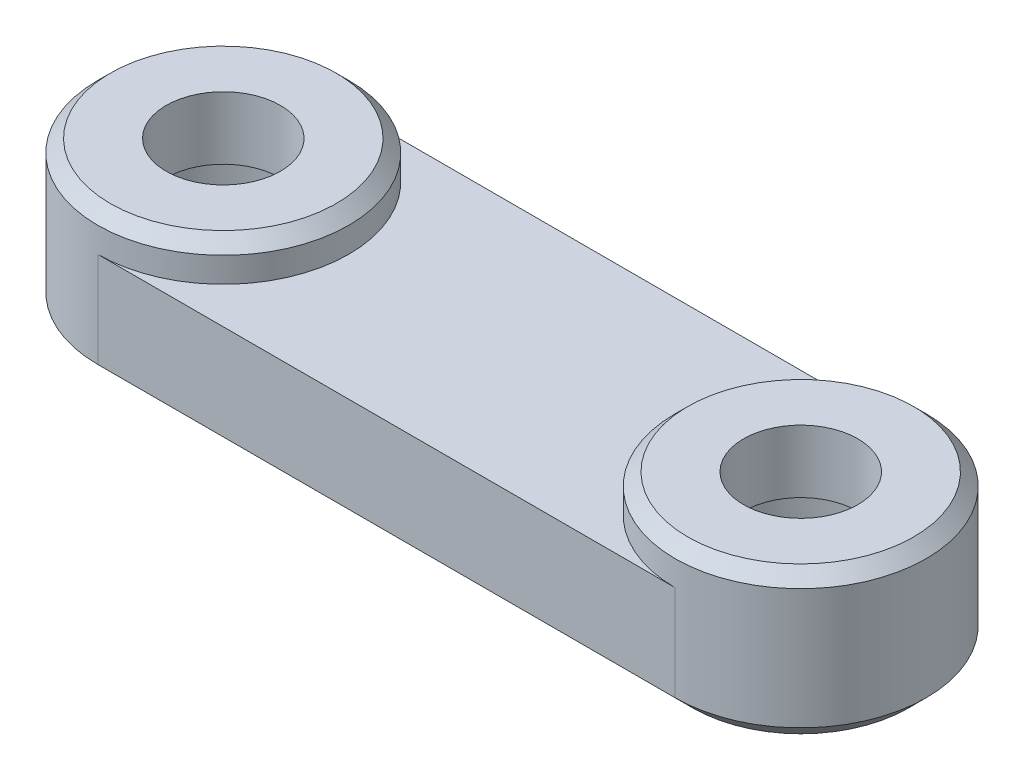
SolidWorks part; units mm, degrees
ref_plane "前视基准面" through (0, 0, 0) normal (0, 0, 1) x (1, 0, 0)
ref_plane "上视基准面" through (0, 0, 0) normal (0, 1, 0) x (1, 0, 0)
ref_plane "右视基准面" through (0, 0, 0) normal (1, 0, 0) x (0, 0, -1)
sketch "草图1" plane through (0, 0, 0) normal (0, 1, 0) x (1, 0, 0)
  line L0 (0, 0) -> (23, 0) construction
  line L1 (0, 5) -> (23, 5)
  line L2 (0, -5) -> (23, -5)
  arc A0 (0, 5) -> (0, -5) centre (0, 0) ccw
  arc A1 (23, -5) -> (23, 5) centre (23, 0) ccw
  point P3 (11.5, 0)
  dimension "D1" = 23
  dimension "D2" = 10
extrude "凸台-拉伸1" add sketch "草图1" along normal blind 6
sketch "草图2" plane through (0, 0, 0) normal (0, 0, 1) x (1, 0, 0)
  line L0 (0, 0) -> (0, 11.3662) construction
  line L1 (-4, 0) -> (-4, 3.5)
  line L2 (-5, 0) -> (0, 0) construction
  line L3 (-4, 3.5) -> (-2.275, 3.5)
  line L4 (-2.275, 3.5) -> (-2.275, 6)
  line L5 (0, 6) -> (-5, 6) construction
  line L6 (-2.275, 6) -> (0, 6)
  line L7 (-4, 0) -> (0, 0)
  line L8 (0, 0) -> (0, 6)
  dimension "D1" = 8
  dimension "D2" = 3.5
  dimension "D3" = 4.55
revolve "切除-旋转1" cut sketch "草图2" angle 360 about L0
sketch "草图3" plane through (0, 0, 0) normal (0, 0, 1) x (1, 0, 0)
  line L0 (23, 0) -> (23, 9.724) construction
  line L1 (23, 0) -> (19, 0)
  line L2 (0, 0) -> (23, 0) construction
  line L3 (19, 0) -> (19, 3.5)
  line L4 (19, 3.5) -> (20.725, 3.5)
  line L5 (20.725, 3.5) -> (20.725, 6)
  line L6 (0, 6) -> (23, 6) construction
  line L7 (20.725, 6) -> (23, 6)
  line L8 (23, 0) -> (23, 6)
  dimension "D1" = 8
  dimension "D2" = 3.5
  dimension "D3" = 4.55
revolve "切除-旋转2" cut sketch "草图3" angle 360 about L0
sketch "草图4" plane through (0, 6, 0) normal (0, 1, 0) x (1, 0, 0)
  line L1 (52.0748, 24.9894) -> (-22.7163, 24.9894)
  line L2 (52.0748, 24.9894) -> (52.0748, -22.1578)
  line L3 (52.0748, -22.1578) -> (-22.7163, -22.1578)
  line L4 (-22.7163, 24.9894) -> (-22.7163, -22.1578)
  circle A0 centre (23, 0) radius 5
  circle A1 centre (0, 0) radius 5
  dimension "D1" = 10
  dimension "D2" = 10
extrude "切除-拉伸1" cut sketch "草图4" against normal blind 1.5
chamfer "倒角1" distance 0.5 angle 45 2 edges at (0, 6, 5) (23, 6, 5)
chamfer "倒角2" distance 0.7 angle 45 4 edges at (11.5, 0, -5) (-5, 0, 0) (28, 0, 0) (11.5, 0, 5)
